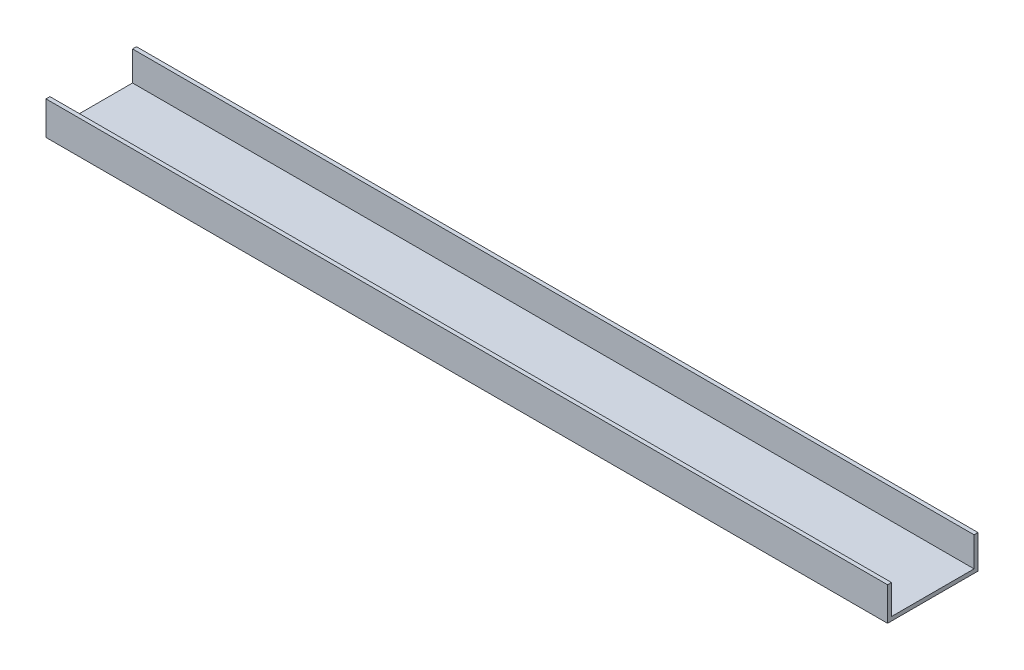
SolidWorks part; units mm, degrees
ref_plane "Plan de face" through (0, 0, 0) normal (0, 0, 1) x (1, 0, 0)
ref_plane "Plan de dessus" through (0, 0, 0) normal (0, 1, 0) x (1, 0, 0)
ref_plane "Plan de droite" through (0, 0, 0) normal (1, 0, 0) x (0, 0, -1)
sketch "Sketch2" plane through (0, 0, 0) normal (1, 0, 0) x (0, 0, -1)
  line L0 (-4, 4.25) -> (-4, -3.25)
  line L1 (18, -4.25) -> (-5, -4.25)
  line L2 (18, -4.25) -> (18, 4.25)
  line L3 (18, 4.25) -> (17, 4.25)
  line L4 (-5, -4.25) -> (-5, 4.25)
  line L7 (-4, -3.25) -> (17, -3.25)
  line L8 (17, -3.25) -> (17, 4.25)
  line L9 (-4, 4.25) -> (-5, 4.25)
  point P0 (0, 0)
  dimension "D1" = 8.5
  dimension "D2" = 23
  dimension "D3" = 1
  dimension "D4" = 1
  dimension "D5" = 1
extrude "Boss-Extrude1" add sketch "Sketch2" along normal blind 214
